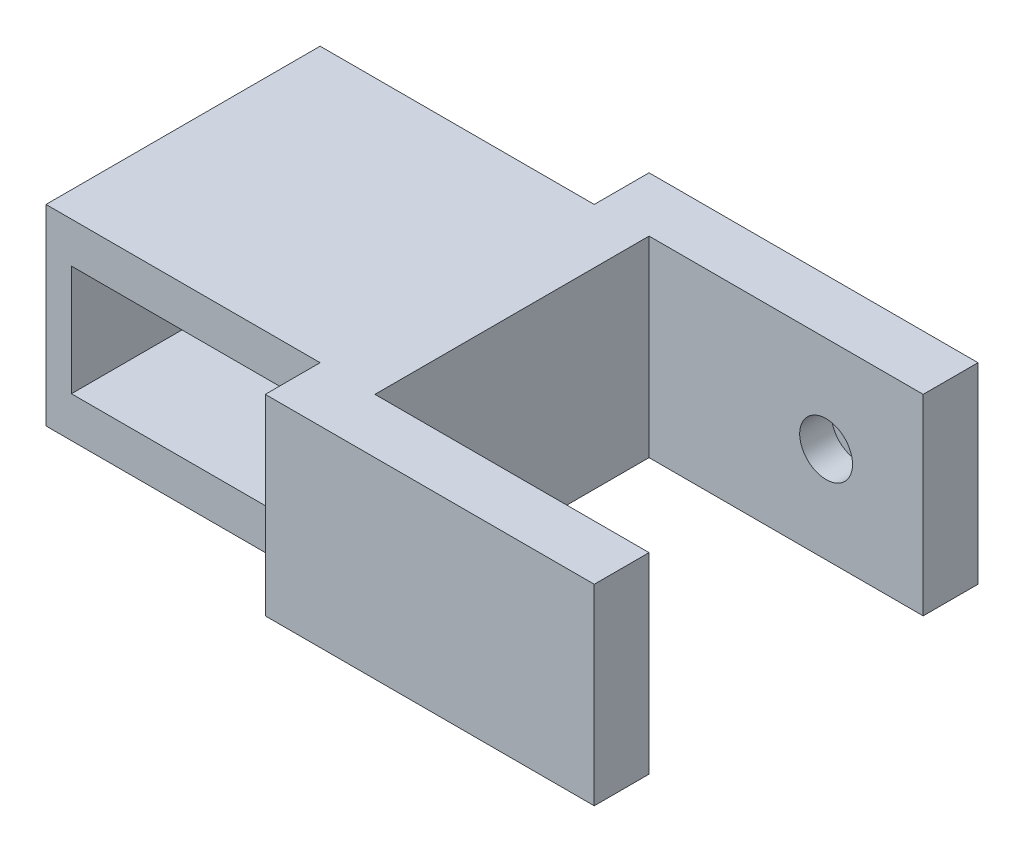
SolidWorks part; units mm, degrees
ref_plane "Front" through (0, 0, 0) normal (0, 0, 1) x (1, 0, 0)
ref_plane "Top" through (0, 0, 0) normal (0, 1, 0) x (1, 0, 0)
ref_plane "Right" through (0, 0, 0) normal (1, 0, 0) x (0, 0, -1)
sketch "Sketch2" plane through (0, 0, 0) normal (0, 0, 1) x (1, 0, 0)
  line L1 (-25, 17.5) -> (25, 17.5)
  line L2 (-25, 17.5) -> (-25, -17.5)
  line L3 (-25, -17.5) -> (25, -17.5)
  line L4 (25, 17.5) -> (25, -17.5)
  line L5 (-25, 17.5) -> (25, -17.5) construction
  line L6 (-25, -17.5) -> (25, 17.5) construction
  point P0 (0, 0)
  dimension "D1" = 50
  dimension "D2" = 35
extrude "Boss-Extrude1" add sketch "Sketch2" along normal blind 50
sketch "Sketch3" plane through (0, 0, 50) normal (0, 0, 1) x (1, 0, 0)
  line L1 (-20.36, 10.085) -> (20.36, 10.085)
  line L2 (-20.36, 10.085) -> (-20.36, -10.085)
  line L3 (-20.36, -10.085) -> (20.36, -10.085)
  line L4 (20.36, 10.085) -> (20.36, -10.085)
  line L5 (-20.36, 10.085) -> (20.36, -10.085) construction
  line L6 (-20.36, -10.085) -> (20.36, 10.085) construction
  point P0 (0, 0)
  dimension "D1" = 40.72
  dimension "D2" = 20.17
extrude "Cut-Extrude1" cut sketch "Sketch3" against normal blind 28.82
sketch "Sketch4" plane through (0, 17.5, 0) normal (0, 1, 0) x (1, 0, 0)
  line L1 (25, -50) -> (25, 0) construction
  line L2 (25, -50) -> (25, 0)
  line L4 (35, -50) -> (35, 0)
  line L5 (35, 0) -> (85, 0)
  line L6 (85, 0) -> (85, 10)
  line L7 (85, 10) -> (25, 10)
  line L11 (85, -60) -> (25, -60)
  line L12 (85, -50) -> (85, -60)
  line L13 (35, -50) -> (85, -50)
  line L15 (25, 10) -> (25, 0)
  line L16 (25, -60) -> (25, -50)
  dimension "D3" = 50
  dimension "D4" = 10
extrude "Boss-Extrude2" add sketch "Sketch4" against normal up to surface (35 mm away) up to face at (0, -17.5, 25)
sketch "Sketch5" plane through (0, 0, 0) normal (0, 0, 1) x (1, 0, 0)
  circle A0 centre (67.2942, 0) radius 4.8173
extrude "Cut-Extrude2" cut sketch "Sketch5" against normal blind 5.82
